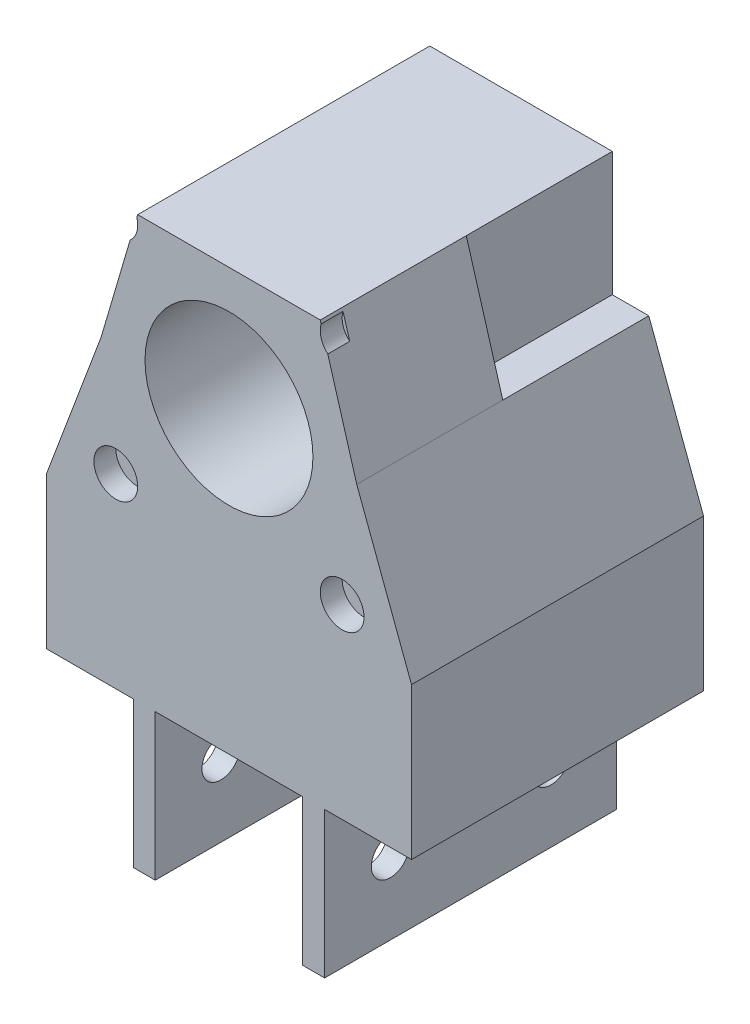
SolidWorks part; units mm, degrees
ref_plane "前视基准面" through (0, 0, 0) normal (0, 0, 1) x (1, 0, 0)
ref_plane "上视基准面" through (0, 0, 0) normal (0, 1, 0) x (1, 0, 0)
ref_plane "右视基准面" through (0, 0, 0) normal (1, 0, 0) x (0, 0, -1)
other "Configuration Table"
sketch "草图1" plane through (0, 0, 0) normal (0, 0, 1) x (1, 0, 0)
  line L0 (0, -39.6057) -> (0, 25.2485) construction
  line L9 (10.1, -25.375) -> (13.1, -25.375)
  line L10 (-25, -5.375) -> (-13.1, -5.375)
  line L11 (-25, -5.375) -> (-25, 5.375)
  line L12 (-25, 5.375) -> (25, 5.375)
  line L13 (25, -5.375) -> (25, 5.375)
  line L14 (-25, -5.375) -> (25, 5.375) construction
  line L15 (-25, 5.375) -> (25, -5.375) construction
  line L16 (-10.1, -5.375) -> (10.1, -5.375)
  line L17 (-13.1, -5.375) -> (-13.1, -25.375)
  line L18 (-13.1, -25.375) -> (-10.1, -25.375)
  line L19 (13.1, -5.375) -> (13.1, -25.375)
  line L21 (-10.1, -25.375) -> (-10.1, -5.375)
  line L22 (-10.1, -5.375) -> (10.1, -5.375)
  line L23 (10.1, -25.375) -> (10.1, -5.375)
  line L24 (-8.4435, -45.2703) -> (10.1, -5.375) construction
  line L25 (-10.1, -5.375) -> (10.5079, -49.7116) construction
  line L26 (-10.1, -5.375) -> (10.1, -5.375)
  line L27 (13.1, -5.375) -> (25, -5.375)
  point P2 (0, 0)
  point P12 (0, -27.1045)
  dimension "D1" = 50
  dimension "D2" = 10.75
  dimension "D3" = 20
  dimension "D4" = 3
  dimension "D5" = 20.2
extrude "凸台-拉伸1" add sketch "草图1" along normal blind 40 contours L19 L27 L13 L12 L11 L10 L17 L18 L21 L16 L23 L9
sketch "草图2" plane through (0, 0, 0) normal (0, 0, -1) x (-1, 0, 0)
  line L0 (0, -5.375) -> (0, 67.3086) construction
  line L1 (10.1, -5.375) -> (-10.1, -5.375) construction
  line L2 (25, 5.375) -> (-25, 5.375) construction
  line L3 (-12.5, 5.375) -> (12.5, 5.375)
  line L4 (-12.5, 5.375) -> (-12.5, 52.375)
  line L5 (-12.5, 52.375) -> (12.5, 52.375)
  line L6 (12.5, 5.375) -> (12.5, 52.375)
  line M14 (25, 5.375) -> (-25, 5.375)
  dimension "D1" = 47
  dimension "D2" = 25
extrude "凸台-拉伸2" add sketch "草图2" against normal up to surface (40 mm away) contours L6 L5 L4 M14 up to face at (0, -10.25, 40)
hole_wizard "孔3" positions "草图9" profile "草图8" legacy end condition through all
sketch "草图9" plane through (0, 0, 40) normal (0, 0, 1) x (1, 0, 0)
  line L0 (0, -5.375) -> (0, 52.375) construction
  line L1 (-10.1, -5.375) -> (10.1, -5.375) construction
  line L2 (12.5, 52.375) -> (-12.5, 52.375) construction
  line L4 (12.5, 5.375) -> (25, 5.375) construction
  point P0 (0, 35.625)
  dimension "D1" = 30.25
sketch "草图8" plane through (0, 35.625, 40) normal (1, 0, 0) x (0, -1, 0)
  line L0 (0, 0) -> (0, 40)
  line L1 (0, 40) -> (11.5, 40)
  line L2 (11.5, 40) -> (11.5, 0)
  line L3 (11.5, 0) -> (0, 0)
  line L4 (0, 110) -> (0, -10) construction
  dimension "直径" = 23
  dimension "深度" = 40
sketch "草图10" plane through (0, 0, 40) normal (0, 0, 1) x (1, 0, 0)
  line L0 (12.5, 35.375) -> (17.5, 35.375)
  line L1 (12.5, 5.375) -> (12.5, 52.375) construction
  line L2 (17.5, 35.375) -> (25, 15.375)
  line L3 (25, 15.375) -> (25, 5.375)
  line L4 (12.5, 35.375) -> (12.5, 5.375)
  line L5 (12.5, 5.375) -> (25, 5.375)
  line L6 (0, 52.375) -> (0, -5.375) construction
  line L7 (12.5, 52.375) -> (-12.5, 52.375) construction
  line L8 (-10.1, -5.375) -> (10.1, -5.375) construction
  line L9 (-12.5, 35.375) -> (-12.5, 5.375)
  line L10 (-12.5, 35.375) -> (-17.5, 35.375)
  line L11 (-17.5, 35.375) -> (-25, 15.375)
  line L12 (-25, 15.375) -> (-25, 5.375)
  line L13 (-12.5, 5.375) -> (-25, 5.375)
  dimension "D1" = 30
  dimension "D2" = 5
  dimension "D3" = 10
extrude "凸台-拉伸3" add sketch "草图10" against normal up to surface (40 mm away) up to face at (11.5, 35.625, 0)
sketch "草图12" plane through (0, 0, 40) normal (0, 0, 1) x (1, 0, 0)
  line L0 (12.5, 52.375) -> (17.5, 35.375)
  line L1 (25, 15.375) -> (17.5, 35.375) construction
  line L2 (17.5, 35.375) -> (12.5, 35.375)
  line L3 (12.5, 35.375) -> (12.5, 52.375)
  line L4 (-12.5, 52.375) -> (-17.5, 35.375)
  line L5 (-17.5, 35.375) -> (-12.5, 35.375)
  line L6 (-12.5, 35.375) -> (-12.5, 52.375)
extrude "凸台-拉伸5" add sketch "草图12" against normal blind 20
hole_wizard "孔4" positions "草图13" profile "草图14" legacy end condition through all
sketch "草图13" plane through (13.1, 0, 0) normal (1, 0, 0) x (0, 0, -1)
  line L0 (-40, -5.375) -> (0, -5.375) construction
  line L4 (0, -5.375) -> (0, -25.375) construction
  line L5 (-40, -5.375) -> (-40, -25.375) construction
  point P0 (-31, -15.375)
  point P2 (-9, -15.375)
  dimension "D1" = 10
  dimension "D2" = 10
  dimension "D3" = 9
  dimension "D4" = 9
sketch "草图14" plane through (13.1, -15.375, 31) normal (0, 1, 0) x (0, 0, -1)
  line L0 (0, 0) -> (0, 38.1)
  line L1 (0, 38.1) -> (2.6, 38.1)
  line L2 (2.6, 38.1) -> (2.6, 0)
  line L3 (2.6, 0) -> (0, 0)
  line L4 (0, 110) -> (0, -10) construction
  dimension "直径" = 5.2
  dimension "深度" = 38.1
sketch "草图15" plane through (0, 0, 40) normal (0, 0, 1) x (1, 0, 0)
  circle A0 centre (-15.5, 51.125) radius 3
  circle A1 centre (15.5, 51.125) radius 3
  circle A2 centre (-15.5, 20.125) radius 3
  circle A3 centre (15.5, 20.125) radius 3
  dimension "D1" = 6
  dimension "D2" = 6
  dimension "D3" = 6
  dimension "D4" = 6
extrude "切除-拉伸1" cut sketch "草图15" against normal blind 3
